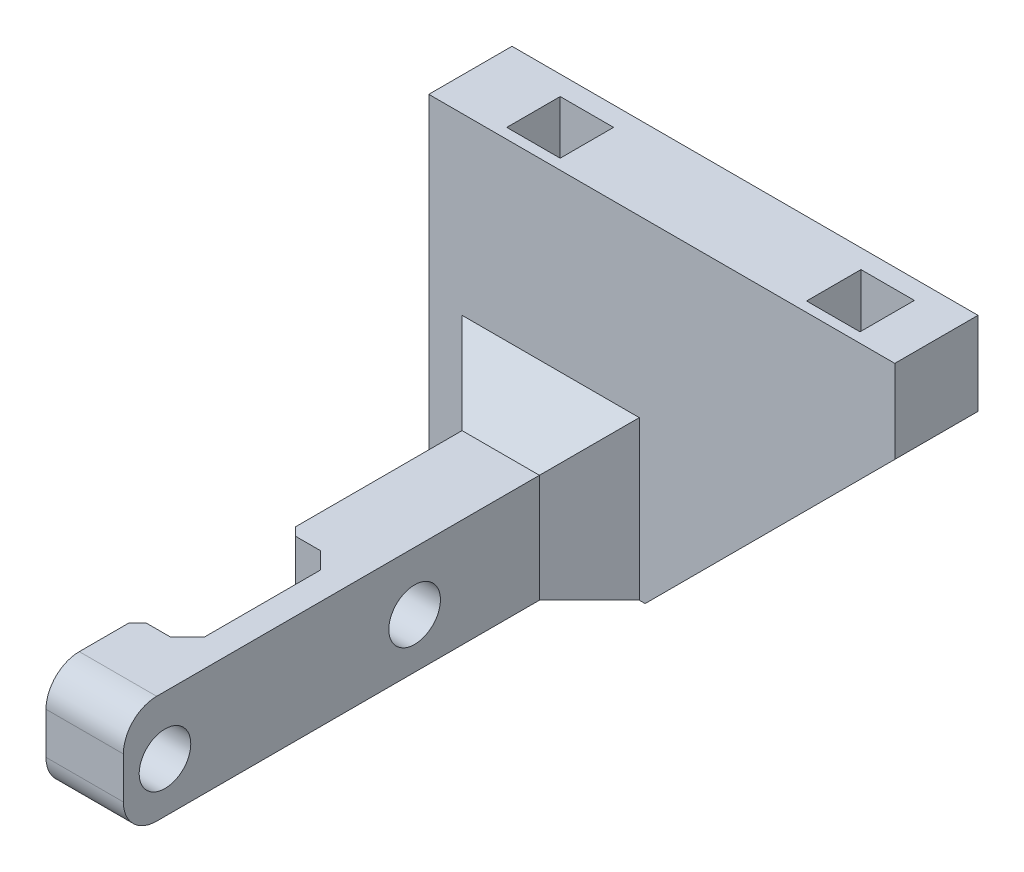
SolidWorks part; units mm, degrees
ref_plane "Front Plane" through (0, 0, 0) normal (0, 0, 1) x (1, 0, 0)
ref_plane "Top Plane" through (0, 0, 0) normal (0, 1, 0) x (1, 0, 0)
ref_plane "Right Plane" through (0, 0, 0) normal (1, 0, 0) x (0, 0, -1)
sketch "Sketch1" plane through (0, 0, 0) normal (0, 1, 0) x (1, 0, 0)
  line L1 (0, 0) -> (28, 0)
  line L2 (0, 0) -> (0, 5)
  line L3 (0, 5) -> (28, 5)
  line L4 (28, 0) -> (28, 5)
  dimension "D1" = 5
  dimension "D2" = 28
extrude "Boss-Extrude1" add sketch "Sketch1" along normal blind 20
chamfer "Chamfer1" distance 15 angle 45 1 edges at (28, 0, -2.5)
sketch "Sketch2" plane through (0, 0, 0) normal (0, 0, 1) x (1, 0, 0)
  line L0 (5, 18) -> (5, 2) construction
  line L1 (5, 18) -> (5, 2)
  line L2 (0, 0) -> (13, 0) construction
  line L3 (5, 6.5) -> (9.6488, 6.5)
  line L4 (5, 6.5) -> (5, 0)
  line L5 (5, 0) -> (9.6488, 0)
  line L6 (9.6488, 6.5) -> (9.6488, 0)
  line M5 (0, 0) -> (13, 0)
  dimension "D1" = 6.5
extrude "Boss-Extrude2" add sketch "Sketch2" along normal blind 28 contours L6 L3 L1 L4 M5
sketch "Sketch3" plane through (0, 0, 0) normal (0, -1, 0) x (1, 0, 0)
  line L0 (5, 28) -> (5, 0) construction
  line L1 (5, 22.5) -> (8, 22.5)
  line L2 (5, 22.5) -> (5, 13.5)
  line L3 (5, 13.5) -> (8, 13.5)
  line L4 (8, 22.5) -> (8, 13.5)
  dimension "D1" = 3
  dimension "D2" = 1
  dimension "D3" = 1
extrude "Cut-Extrude1" cut sketch "Sketch3" against normal blind 12.8
chamfer "Chamfer2" distance 1 angle 45 2 edges at (8, 3.25, 13.5) (8, 3.25, 22.5)
fillet "Fillet1" radius 2 2 edges at (7.3244, 6.5, 28) (7.3244, 0, 28)
chamfer "Chamfer3" distance 0.5 angle 45 2 edges at (5, 3.25, 22.5) (5, 3.25, 13.5)
sketch "Sketch4" plane through (5, 0, 0) normal (-1, 0, 0) x (0, 0, 1)
  arc A0 (25.5, 1.45) -> (25.5, 4.55) centre (25.5, 3) ccw construction
  arc A1 (25.5, 4.55) -> (25.5, 1.45) centre (25.5, 3) ccw construction
  arc A2 (10.5, 4.55) -> (10.5, 1.45) centre (10.5, 3) ccw construction
  arc A3 (10.5, 1.45) -> (10.5, 4.55) centre (10.5, 3) ccw construction
  arc A4 (25.5, 1.45) -> (25.5, 4.55) centre (25.5, 3) ccw
  arc A5 (25.5, 4.55) -> (25.5, 1.45) centre (25.5, 3) ccw
  arc A6 (10.5, 4.55) -> (10.5, 1.45) centre (10.5, 3) ccw
  arc A7 (10.5, 1.45) -> (10.5, 4.55) centre (10.5, 3) ccw
extrude "Cut-Extrude2" cut sketch "Sketch4" against normal blind 12.8
chamfer "Chamfer4" distance 3 angle 45 2 edges at (5, 3.25, 0) (9.6488, 3.25, 0)
chamfer "Chamfer5" distance 3 angle 45 1 edges at (7.3244, 6.5, 0)
sketch "Sketch8" plane through (0, 20, 0) normal (0, 1, 0) x (1, 0, 0)
  line L0 (22.254, 1.284) -> (22.254, 1.158) construction
  line L1 (22.254, 0.746) -> (22.254, 1.158) construction
  line L2 (22.254, 3.714) -> (22.254, 1.284) construction
  line L3 (22.254, 3.714) -> (25.164, 3.714) construction
  line L4 (25.164, 3.714) -> (25.164, 0.75) construction
  line L5 (25.164, 0.746) -> (24.43, 0.746) construction
  line L6 (24.43, 0.746) -> (22.254, 0.746) construction
  line L7 (4.214, 2.802) -> (4.214, 2.092) construction
  line L8 (4.214, 2.092) -> (4.214, 0.772) construction
  line L9 (4.858, 0.772) -> (4.214, 0.772) construction
  line L10 (6.602, 0.772) -> (7.122, 0.772) construction
  line L11 (4.858, 0.772) -> (6.602, 0.772) construction
  line L12 (7.122, 0.772) -> (7.122, 3.484) construction
  line L13 (7.122, 3.682) -> (7.122, 3.484) construction
  line L14 (4.214, 3.682) -> (4.214, 2.802) construction
  line L15 (6.328, 3.682) -> (4.214, 3.682) construction
  line L16 (7.122, 3.682) -> (6.328, 3.682) construction
  line L17 (22.254, 1.284) -> (22.254, 1.158)
  line L18 (22.254, 0.746) -> (22.254, 1.158)
  line L19 (22.254, 3.714) -> (22.254, 1.284)
  line L20 (22.254, 3.714) -> (25.164, 3.714)
  line L21 (25.164, 3.714) -> (25.164, 0.75)
  line L22 (25.164, 0.746) -> (24.43, 0.746)
  line L23 (24.43, 0.746) -> (22.254, 0.746)
  line L24 (4.214, 2.802) -> (4.214, 2.092)
  line L25 (4.214, 2.092) -> (4.214, 0.772)
  line L26 (4.858, 0.772) -> (4.214, 0.772)
  line L27 (6.602, 0.772) -> (7.122, 0.772)
  line L28 (4.858, 0.772) -> (6.602, 0.772)
  line L29 (7.122, 0.772) -> (7.122, 3.484)
  line L30 (7.122, 3.682) -> (7.122, 3.484)
  line L31 (4.214, 3.682) -> (4.214, 2.802)
  line L32 (6.328, 3.682) -> (4.214, 3.682)
  line L33 (7.122, 3.682) -> (6.328, 3.682)
  line L34 (25.252, 3.714) -> (22.254, 3.714) construction
  line L35 (25.164, 0.746) -> (22.254, 0.746)
  line L36 (25.164, 0.746) -> (25.164, 3.714)
  line L37 (25.164, 3.714) -> (22.254, 3.714)
  line L38 (22.254, 0.746) -> (22.254, 3.714)
  line L39 (25.314, 0.596) -> (22.104, 0.596)
  line L40 (25.314, 0.596) -> (25.314, 3.864)
  line L41 (25.314, 3.864) -> (22.104, 3.864)
  line L42 (22.104, 0.596) -> (22.104, 3.864)
  line L44 (4.064, 0.622) -> (7.272, 0.622)
  line L45 (4.064, 0.622) -> (4.064, 3.832)
  line L46 (4.064, 3.832) -> (7.272, 3.832)
  line L47 (7.272, 0.622) -> (7.272, 3.832)
  dimension "D1" = 0.15
  dimension "D2" = 0.15
  dimension "D3" = 0.15
  dimension "D4" = 0.15
  dimension "D5" = 0.15
  dimension "D6" = 0.15
  dimension "D7" = 0.15
  dimension "D8" = 0.15
extrude "Cut-Extrude3" cut sketch "Sketch8" against normal blind 5.4 contours L44 L47 L46 L45 L33 L30 L29 L27 L28 L26 L25 L24 L31 L32 | L30 L33 L32 L31 L24 L25 L26 L28 L27 L29 | L22 L36 L21 L20 L19 L17 L18 L23 | L42 L39 L40 L41 L36 L22 L23 L18 L17 L19 L20 L21
